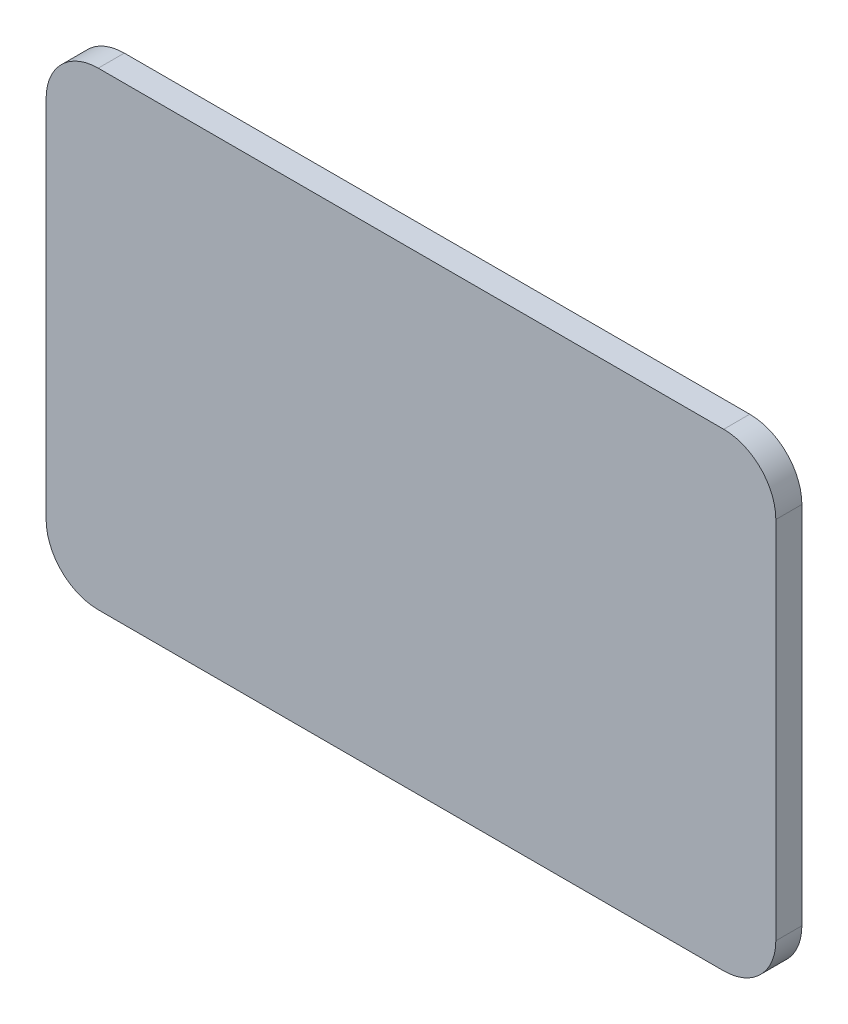
SolidWorks part; units mm, degrees
ref_plane "Plano frontal" through (0, 0, 0) normal (0, 0, 1) x (1, 0, 0)
ref_plane "Plano superior" through (0, 0, 0) normal (0, 1, 0) x (1, 0, 0)
ref_plane "Plano direito" through (0, 0, 0) normal (1, 0, 0) x (0, 0, -1)
sketch "Esboço1" plane through (0, 0, 0) normal (0, 0, 1) x (1, 0, 0)
  line L0 (-11.3373, -8.8786) -> (12.6627, -8.8786)
  line L1 (14.6627, -6.8786) -> (14.6627, 7.1214)
  line L2 (12.6627, 9.1214) -> (-11.3373, 9.1214)
  line L3 (-13.3373, 7.1214) -> (-13.3373, -6.8786)
  arc A0 (-13.3373, -6.8786) -> (-11.3373, -8.8786) centre (-11.3373, -6.8786) ccw
  arc A1 (12.6627, -8.8786) -> (14.6627, -6.8786) centre (12.6627, -6.8786) ccw
  arc A2 (14.6627, 7.1214) -> (12.6627, 9.1214) centre (12.6627, 7.1214) ccw
  arc A3 (-11.3373, 9.1214) -> (-13.3373, 7.1214) centre (-11.3373, 7.1214) ccw
extrude "Ressalto-extrusão1" add sketch "Esboço1" along normal blind 1
